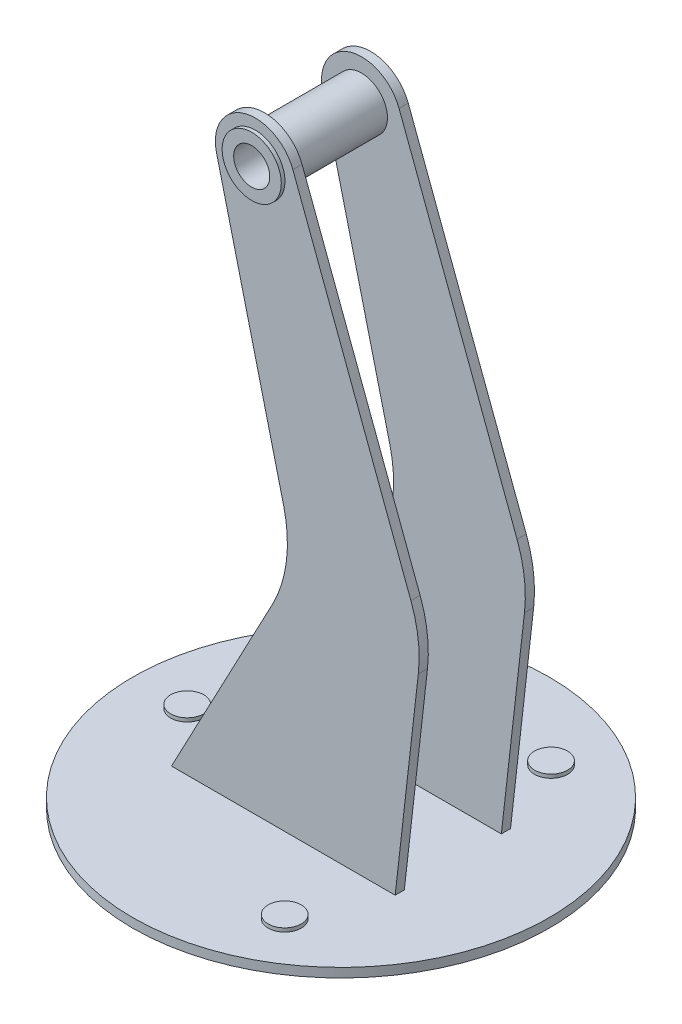
SolidWorks part; units mm, degrees
ref_plane "Front Plane" through (0, 0, 0) normal (0, 0, 1) x (1, 0, 0)
ref_plane "Top Plane" through (0, 0, 0) normal (0, 1, 0) x (1, 0, 0)
ref_plane "Right Plane" through (0, 0, 0) normal (1, 0, 0) x (0, 0, -1)
sketch "Sketch1" plane through (0, 0, 0) normal (0, 0, 1) x (1, 0, 0)
  line L0 (13.5588, -204.7427) -> (81, -77.4535)
  line L1 (81, -77.4535) -> (38.2542, 95.7407)
  line L2 (13.5588, -204.7427) -> (135.2709, -204.7427)
  line L3 (135.2709, -204.7427) -> (149.7684, -77.4535)
  line L4 (149.7684, -77.4535) -> (79.6087, 109.2995)
  circle A0 centre (59.22, 101.6398) radius 9.8101
  arc A1 (79.6087, 109.2995) -> (38.2542, 95.7407) centre (59.22, 101.6398) ccw
extrude "Boss-Extrude1" add sketch "Sketch1" along normal blind 5
sketch "Sketch2" plane through (0, 0, 62.7668) normal (0, 0, -1) x (-1, 0, 0)
  line L5 (-135.2709, -204.7427) -> (-13.5588, -204.7427)
  line L6 (-13.5588, -204.7427) -> (-81, -77.4535)
  line L7 (-81, -77.4535) -> (-38.2542, 95.7407)
  line L8 (-79.6087, 109.2995) -> (-149.7684, -77.4535)
  line L9 (-149.7684, -77.4535) -> (-135.2709, -204.7427)
  line L10 (-135.2709, -204.7427) -> (-13.5588, -204.7427)
  line L11 (-13.5588, -204.7427) -> (-81, -77.4535)
  line L12 (-81, -77.4535) -> (-38.2542, 95.7407)
  line L13 (-79.6087, 109.2995) -> (-149.7684, -77.4535)
  line L14 (-149.7684, -77.4535) -> (-135.2709, -204.7427)
  arc A1 (-38.2542, 95.7407) -> (-79.6087, 109.2995) centre (-59.22, 101.6398) ccw
  arc A2 (-38.2542, 95.7407) -> (-79.6087, 109.2995) centre (-59.22, 101.6398) ccw
  dimension "D1" = 0
extrude "Boss-Extrude2" add sketch "Sketch2" along normal blind 5 separate body
sketch "Sketch3" plane through (0, 0, 5) normal (0, 0, 1) x (1, 0, 0)
  circle A0 centre (59.22, 101.6398) radius 9.8101
extrude "Cut-Extrude1" cut sketch "Sketch3" along normal blind 84
sketch "Sketch4" plane through (0, 0, 5) normal (0, 0, 1) x (1, 0, 0)
  circle A0 centre (59.22, 101.6398) radius 9.8101
  circle A1 centre (59.22, 101.6398) radius 14.0768
extrude "Boss-Extrude3" add sketch "Sketch4" along normal up to surface (52.7668 mm away) up to face at (59.22, 111.45, 57.7668)
sketch "Sketch5" plane through (0, 0, 62.7668) normal (0, 0, 1) x (1, 0, 0)
  circle A0 centre (59.22, 101.6398) radius 9.8101
  circle A1 centre (59.22, 101.6398) radius 16.0901
extrude "Boss-Extrude4" add sketch "Sketch5" along normal blind 2
sketch "Sketch6" plane through (0, 0, 0) normal (0, 0, -1) x (-1, 0, 0)
  circle A0 centre (-59.22, 101.6398) radius 9.8101
  circle A1 centre (-59.22, 101.6398) radius 16.0901
  circle A2 centre (-59.22, 101.6398) radius 16.0901
  dimension "D1" = 0
extrude "Boss-Extrude5" add sketch "Sketch6" along normal blind 2
fillet "Fillet1" radius 70 2 edges at (81, -77.4535, 60.2668) (81, -77.4535, 2.5)
fillet "Fillet2" radius 70 2 edges at (149.7684, -77.4535, 2.5) (149.7684, -77.4535, 60.2668)
sketch "Sketch7" plane through (0, -204.7427, 0) normal (0, -1, 0) x (-1, 0, 0)
  circle A1 centre (-74.4149, -31.3834) radius 113.3367
extrude "Boss-Extrude6" add sketch "Sketch7" along normal blind 5
sketch "Sketch8" plane through (0, -204.7427, 0) normal (0, 1, 0) x (1, 0, 0)
  circle A0 centre (-9.2485, -31.3834) radius 9
  dimension "D1" = 18
extrude "Boss-Extrude7" add sketch "Sketch8" along normal blind 2
pattern_circular "CirPattern1" count 3 over 360 about axis through (74.4149, 0, 31.3834) along (0, 1, 0) of "Boss-Extrude7"
